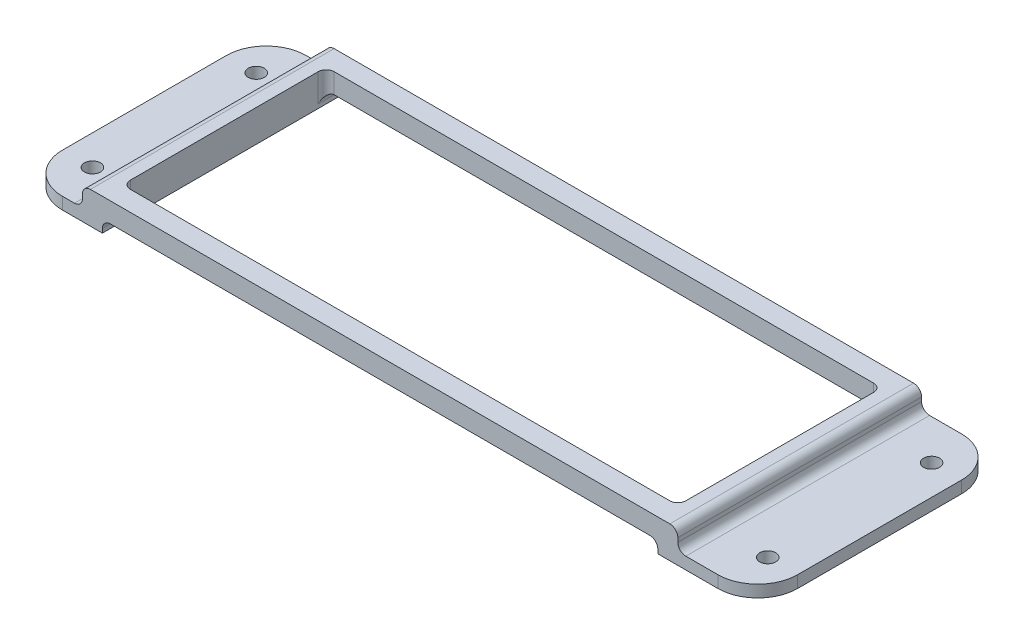
SolidWorks part; units mm, degrees
ref_plane "Front Plane" through (0, 0, 0) normal (0, 0, 1) x (1, 0, 0)
ref_plane "Top Plane" through (0, 0, 0) normal (0, 1, 0) x (1, 0, 0)
ref_plane "Right Plane" through (0, 0, 0) normal (1, 0, 0) x (0, 0, -1)
sketch "Sketch1" plane through (0, 0, 0) normal (0, 1, 0) x (1, 0, 0)
  line L0 (0, 0) -> (184, 0) construction
  line L1 (184, 0) -> (184, 61)
  line L2 (184, 61) -> (0, 61) construction
  line L3 (0, 61) -> (0, 0)
  line L4 (0, 30.5) -> (184, 30.5) construction
  line L5 (15, 56) -> (169, 56) construction
  line L6 (15, 56) -> (15, 5) construction
  line L7 (15, 5) -> (169, 5) construction
  line L8 (169, 56) -> (169, 5) construction
  line L9 (15, 56) -> (169, 5) construction
  line L10 (15, 5) -> (169, 56) construction
  line L11 (184, 30.5) -> (92, 61) construction
  line L12 (92, 61) -> (92, 0) construction
  line L13 (0, 61) -> (20, 61)
  line L14 (20, 61) -> (20, 0)
  line L15 (20, 0) -> (0, 0)
  line L16 (184, 0) -> (159, 0)
  line L17 (159, 0) -> (159, 61)
  line L18 (159, 61) -> (184, 61)
  circle A0 centre (7.5, 10) radius 2
  circle A1 centre (176.5, 10) radius 2
  circle A2 centre (176.5, 51) radius 2
  circle A3 centre (7.5, 51) radius 2
  point P2 (92, 30.5)
  dimension "D5" = 4
  dimension "D1" = 51
  dimension "D2" = 154
  dimension "D3" = 5
  dimension "D4" = 15
  dimension "D6" = 10
  dimension "D7" = 7.5
  dimension "D8" = 5
  dimension "D9" = 10
extrude "Boss-Extrude1" add sketch "Sketch1" along normal blind 3
sketch "Sketch3" plane through (0, 3, 0) normal (0, 1, 0) x (1, 0, 0)
  line L0 (0, 0) -> (20, 0) construction
  line L1 (20, 61) -> (15, 61)
  line L2 (20, 61) -> (20, 0)
  line L3 (20, 0) -> (15, 0)
  line L4 (15, 61) -> (15, 0)
  line L5 (159, 0) -> (184, 0) construction
  line L6 (159, 61) -> (164, 61)
  line L7 (159, 61) -> (159, 0)
  line L8 (159, 0) -> (164, 0)
  line L9 (164, 61) -> (164, 0)
  dimension "D1" = 5
extrude "Boss-Extrude2" add sketch "Sketch3" along normal blind 5
sketch "Sketch4" plane through (20, 0, 0) normal (1, 0, 0) x (0, 0, -1)
  line L0 (0, 3) -> (61, 3) construction
  line L1 (0, 8) -> (5, 8)
  line L2 (0, 8) -> (0, 3)
  line L3 (0, 3) -> (5, 3)
  line L4 (5, 8) -> (5, 3)
  line L6 (61, 8) -> (56, 8)
  line L7 (61, 8) -> (61, 3)
  line L8 (61, 3) -> (56, 3)
  line L9 (56, 8) -> (56, 3)
extrude "Boss-Extrude3" add sketch "Sketch4" along normal up to surface (139 mm away) up to face at (159, 4, -30.5)
fillet "Fillet1" radius 10 4 edges at (184, 1.5, 0) (184, 1.5, -61) (0, 1.5, -61) (0, 1.5, 0)
fillet "Fillet2" radius 2 12 edges at (164, 3, -30.5) (164, 8, -30.5) (15, 3, -30.5) (15, 8, -30.5) (20, 3, -58.5) (20, 5.5, -56) (20, 5.5, -5) (20, 3, -2.5) (159, 5.5, -56) (159, 5.5, -5) (159, 3, -2.5) (159, 3, -58.5)
